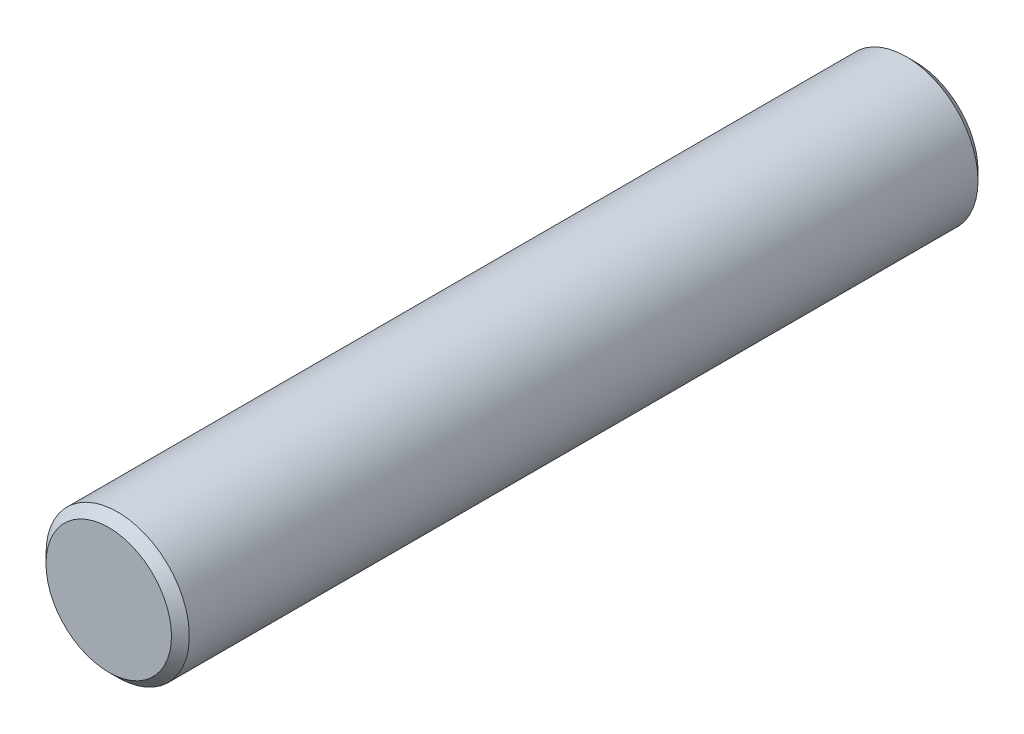
SolidWorks part; units mm, degrees
ref_plane "Plan de face" through (0, 0, 0) normal (0, 0, 1) x (1, 0, 0)
ref_plane "Plan de dessus" through (0, 0, 0) normal (0, 1, 0) x (1, 0, 0)
ref_plane "Plan de droite" through (0, 0, 0) normal (1, 0, 0) x (0, 0, -1)
sketch "Esquisse1" plane through (0, 0, 0) normal (0, 0, 1) x (1, 0, 0)
  circle A0 centre (0, 0) radius 4
  dimension "D1" = 8
extrude "Boss.-Extru.1" add sketch "Esquisse1" along normal blind 45
chamfer "Chanfrein1" distance 0.5 angle 45 2 edges at (4, 0, 0) (4, 0, 45)
